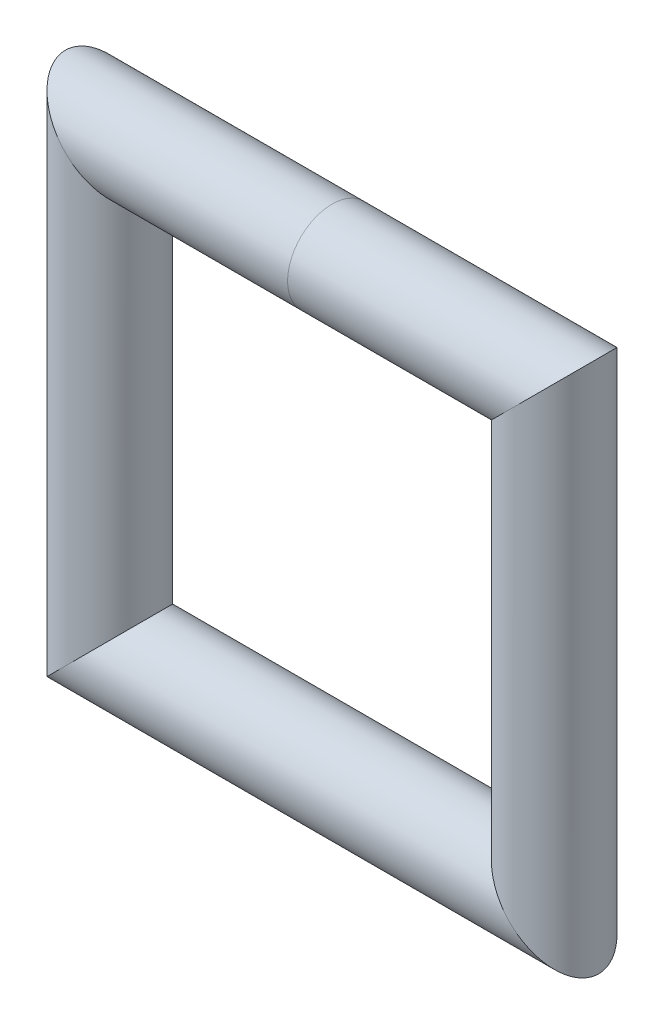
SolidWorks part; units mm, degrees
ref_plane "前视基准面" through (0, 0, 0) normal (0, 0, 1) x (1, 0, 0)
ref_plane "上视基准面" through (0, 0, 0) normal (0, 1, 0) x (1, 0, 0)
ref_plane "右视基准面" through (0, 0, 0) normal (1, 0, 0) x (0, 0, -1)
sketch "草图1" plane through (0, 0, 0) normal (0, 0, 1) x (1, 0, 0)
  line L1 (-25, -25) -> (25, -25)
  line L2 (-25, -25) -> (-25, 25)
  line L3 (-25, 25) -> (25, 25)
  line L4 (25, -25) -> (25, 25)
  line L5 (-25, -25) -> (25, 25) construction
  line L6 (-25, 25) -> (25, -25) construction
  point P0 (0, 0)
  dimension "D1" = 50
  dimension "D2" = 50
sketch "草图2" plane through (0, 0, 0) normal (1, 0, 0) x (0, 0, -1)
  line L0 (0, 25) -> (0, -25) construction
  circle A0 centre (0, 12.5) radius 2.5
  dimension "D1" = 5
sweep "扫描1" add profiles "草图2" path "草图1"
